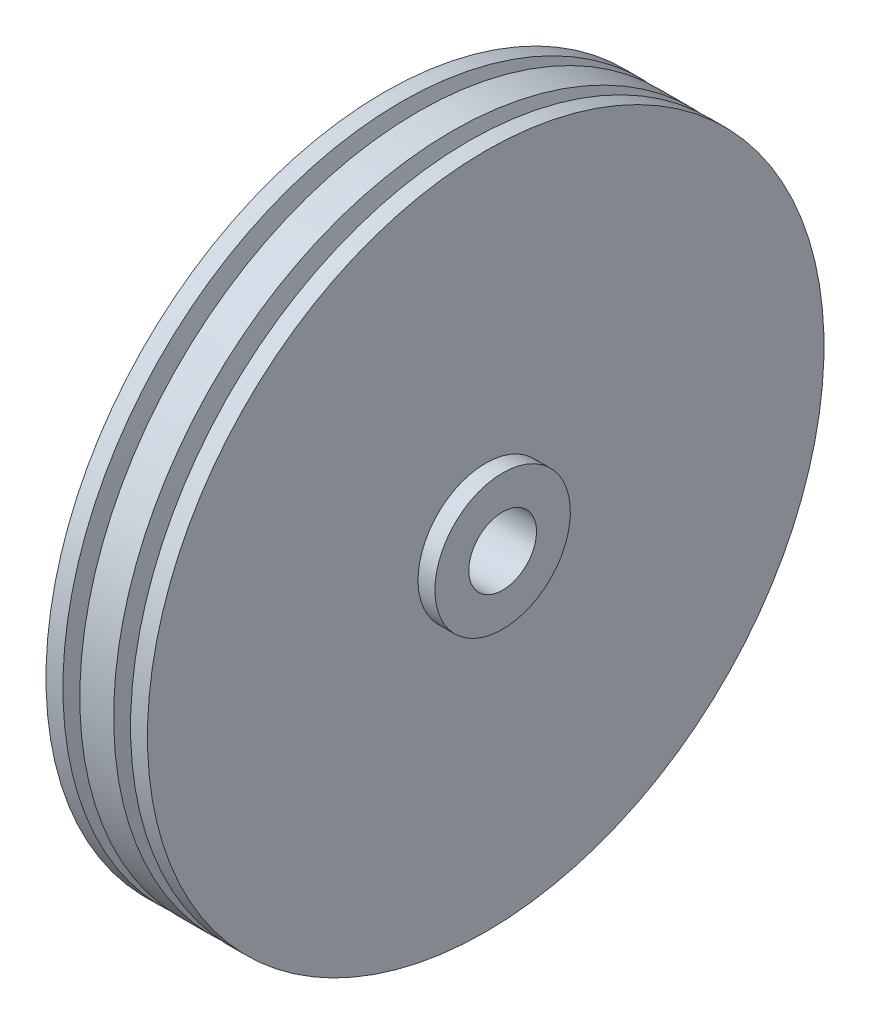
SolidWorks part; units mm, degrees
ref_plane "Alzado" through (0, 0, 0) normal (0, 0, 1) x (1, 0, 0)
ref_plane "Planta" through (0, 0, 0) normal (0, 1, 0) x (1, 0, 0)
ref_plane "Vista lateral" through (0, 0, 0) normal (1, 0, 0) x (0, 0, -1)
sketch "Croquis1" plane through (0, 0, 0) normal (0, 0, 1) x (1, 0, 0)
  line L0 (0, 0) -> (68.9056, 0) construction
  line L1 (68.9056, 0) -> (-115.1801, 0) construction
  line L2 (-15.2242, 10.0164) -> (-35.2242, 10.0164)
  line L3 (-35.2242, 10.0164) -> (-35.2242, 20.0164)
  line L4 (-35.2242, 20.0164) -> (-30.2242, 20.0164)
  line L5 (-30.2242, 20.0164) -> (-30.2242, 80.0164)
  line L6 (-30.2242, 80.0164) -> (-50.2242, 80.0164)
  line L8 (-50.2242, 100.0164) -> (-45.2242, 100.0164)
  line L9 (-15.2242, 10.0164) -> (-15.2242, 20.0164)
  line L10 (-15.2242, 20.0164) -> (-20.2242, 20.0164)
  line L11 (-20.2242, 20.0164) -> (-20.2242, 80.0164)
  line L12 (-20.2242, 80.0164) -> (-20.2242, 100.0164)
  line L13 (-20.2242, 100.0164) -> (-25.2242, 100.0164)
  line L17 (-30.2242, 100.0164) -> (-40.2242, 100.0164)
  line L31 (-45.2242, 100.0164) -> (-42.7242, 90.0164)
  line L32 (-42.7242, 90.0164) -> (-40.2242, 100.0164)
  line L33 (-30.2242, 100.0164) -> (-27.7242, 90.0164)
  line L34 (-27.7242, 90.0164) -> (-25.2242, 100.0164)
  line L42 (-50.2242, 100.0164) -> (-50.2242, 80.0164)
revolve "Revolución3" add sketch "Croquis1" angle 360 about L1
